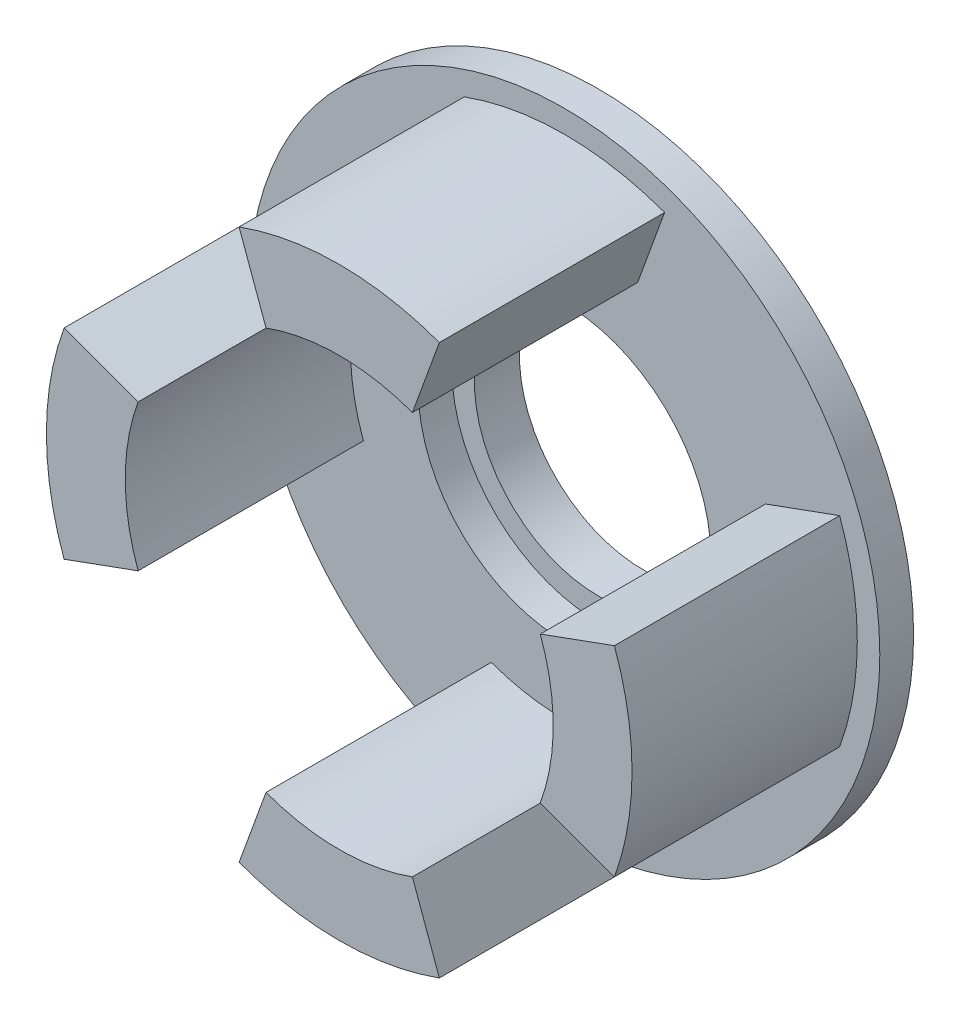
SolidWorks part; units mm, degrees
ref_plane "前视基准面" through (0, 0, 0) normal (0, 0, 1) x (1, 0, 0)
ref_plane "上视基准面" through (0, 0, 0) normal (0, 1, 0) x (1, 0, 0)
ref_plane "右视基准面" through (0, 0, 0) normal (1, 0, 0) x (0, 0, -1)
sketch "草图1" plane through (0, 0, 0) normal (0, 0, 1) x (1, 0, 0)
  circle A0 centre (0, 0) radius 11
  circle A1 centre (0, 0) radius 16
  dimension "D1" = 22
  dimension "D2" = 32
extrude "凸台-拉伸1" add sketch "草图1" along normal blind 4
sketch "草图2" plane through (0, 0, 4) normal (0, 0, 1) x (1, 0, 0)
  circle A0 centre (0, 0) radius 13
  circle A1 centre (0, 0) radius 28
  dimension "D1" = 26
  dimension "D2" = 56
extrude "凸台-拉伸2" add sketch "草图2" along normal blind 3
sketch "草图3" plane through (0, 0, 7) normal (0, 0, 1) x (1, 0, 0)
  line L0 (0, 30.1418) -> (0, 19) construction
  line L1 (-8.8925, 24.432) -> (-6.4984, 17.8542)
  line L2 (8.8925, 24.432) -> (6.4984, 17.8542)
  line L3 (-6.4984, 17.8542) -> (0, 0) construction
  line L4 (0, 19) -> (0, 0) construction
  line L5 (0, 0) -> (0, -32.689) construction
  line L6 (6.4984, 17.8542) -> (0, 0) construction
  line L7 (24.432, 8.8925) -> (17.8542, 6.4984)
  line L8 (24.432, -8.8925) -> (17.8542, -6.4984)
  line L9 (8.8925, -24.432) -> (6.4984, -17.8542)
  line L10 (-8.8925, -24.432) -> (-6.4984, -17.8542)
  line L11 (-24.432, -8.8925) -> (-17.8542, -6.4984)
  line L12 (-24.432, 8.8925) -> (-17.8542, 6.4984)
  arc A0 (6.4984, 17.8542) -> (-6.4984, 17.8542) centre (0, 0) ccw
  arc A1 (8.8925, 24.432) -> (-8.8925, 24.432) centre (0, 0) ccw
  arc A2 (-6.4984, 17.8542) -> (0, -19) centre (0, 0) ccw construction
  arc A3 (0, -19) -> (6.4984, 17.8542) centre (0, 0) ccw construction
  arc A4 (-8.8925, 24.432) -> (0, -26) centre (0, 0) ccw construction
  arc A5 (0, -26) -> (8.8925, 24.432) centre (0, 0) ccw construction
  arc A6 (24.432, -8.8925) -> (24.432, 8.8925) centre (0, 0) ccw
  arc A7 (17.8542, -6.4984) -> (17.8542, 6.4984) centre (0, 0) ccw
  arc A8 (-8.8925, -24.432) -> (8.8925, -24.432) centre (0, 0) ccw
  arc A9 (-6.4984, -17.8542) -> (6.4984, -17.8542) centre (0, 0) ccw
  arc A10 (-24.432, 8.8925) -> (-24.432, -8.8925) centre (0, 0) ccw
  arc A11 (-17.8542, 6.4984) -> (-17.8542, -6.4984) centre (0, 0) ccw
  point P26 (0, 0)
  dimension "D1" = 38
  dimension "D2" = 52
  dimension "D3" = 40
extrude "凸台-拉伸3" add sketch "草图3" along normal blind 20
